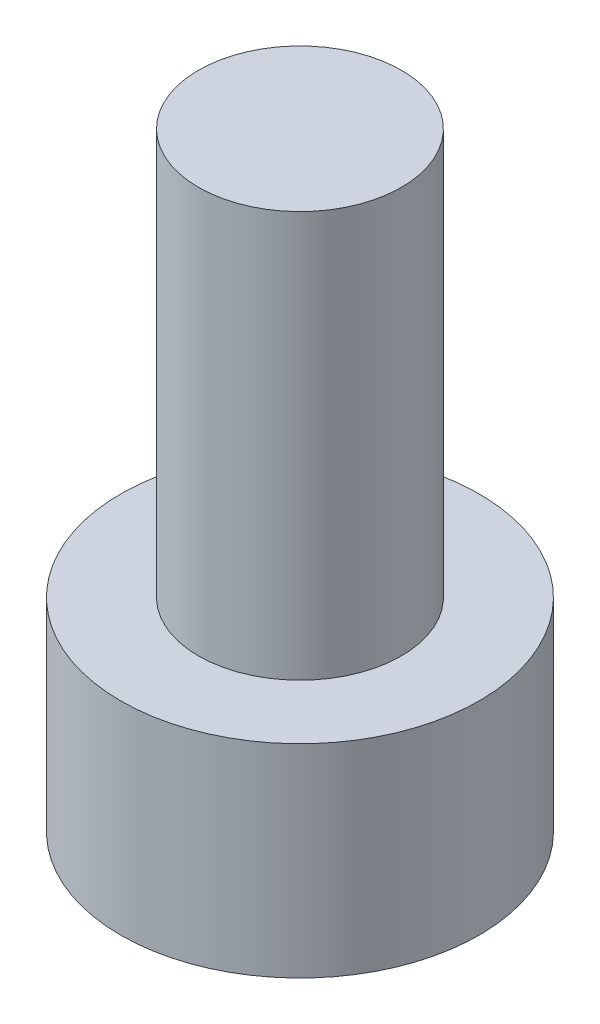
SolidWorks part; units mm, degrees
ref_plane "Front Plane" through (0, 0, 0) normal (0, 0, 1) x (1, 0, 0)
ref_plane "Top Plane" through (0, 0, 0) normal (0, 1, 0) x (1, 0, 0)
ref_plane "Right Plane" through (0, 0, 0) normal (1, 0, 0) x (0, 0, -1)
other "Configuration Table"
sketch "Sketch1" plane through (0, 0, 0) normal (0, 1, 0) x (1, 0, 0)
  line L1 (0.7217, 1.25) -> (-0.7217, 1.25)
  line L2 (-0.7217, 1.25) -> (-1.4434, 0)
  line L3 (-1.4434, 0) -> (-0.7217, -1.25)
  line L4 (-0.7217, -1.25) -> (0.7217, -1.25)
  line L5 (0.7217, -1.25) -> (1.4434, 0)
  line L6 (1.4434, 0) -> (0.7217, 1.25)
  circle A0 centre (0, 0) radius 2.65
  circle A1 centre (0, 0) radius 1.25 construction
  point P3 (0, 0)
  dimension "D1" = 5.3
  dimension "D2" = 2.5
extrude "Boss-Extrude1" add sketch "Sketch1" along normal blind 3
sketch "Sketch2" plane through (0, 3, 0) normal (0, 1, 0) x (1, 0, 0)
  circle A0 centre (0, 0) radius 1.5
  dimension "D1" = 3
extrude "Boss-Extrude2" add sketch "Sketch2" along normal blind 6
